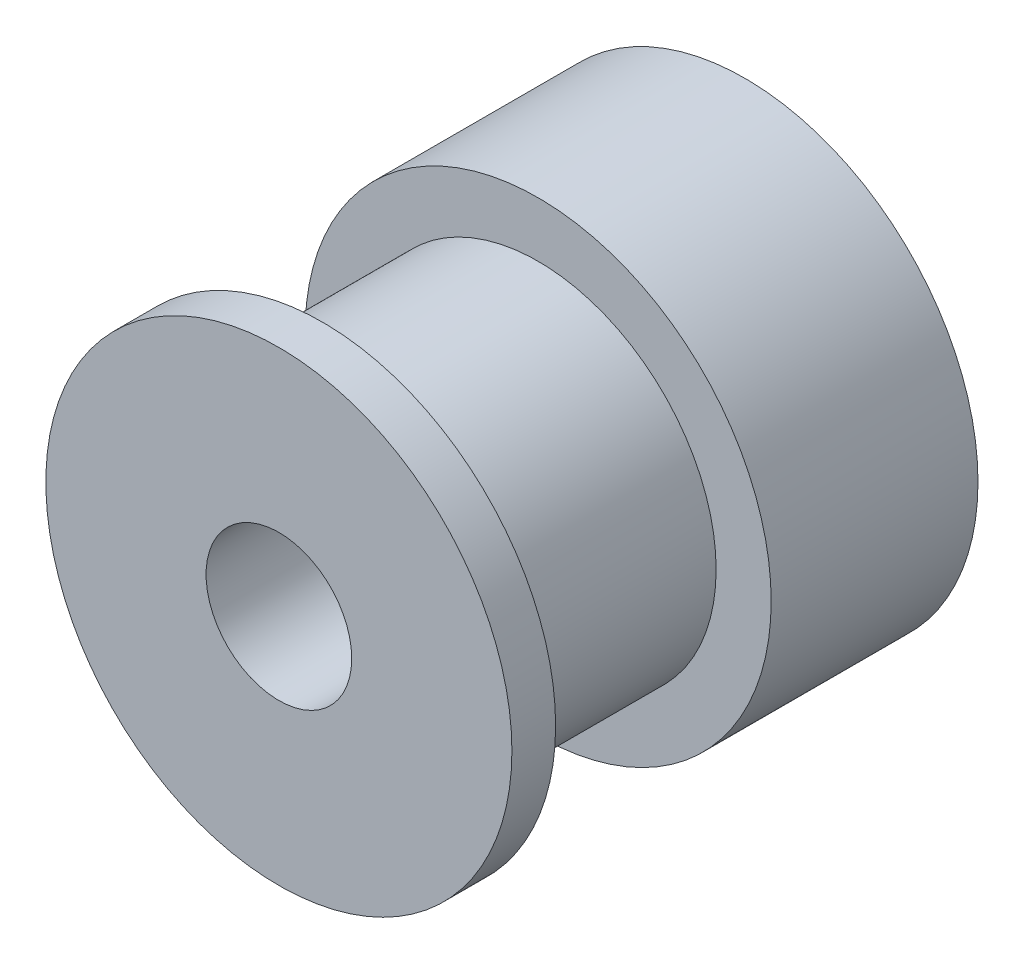
SolidWorks part; units mm, degrees
ref_plane "Front Plane" through (0, 0, 0) normal (0, 0, 1) x (1, 0, 0)
ref_plane "Top Plane" through (0, 0, 0) normal (0, 1, 0) x (1, 0, 0)
ref_plane "Right Plane" through (0, 0, 0) normal (1, 0, 0) x (0, 0, -1)
sketch "Sketch1" plane through (0, 0, 0) normal (0, 0, 1) x (1, 0, 0)
  circle A0 centre (0, 0) radius 8
  dimension "D1" = 16
extrude "Boss-Extrude1" add sketch "Sketch1" along normal blind 7.1
sketch "Sketch2" plane through (0, 0, 7.1) normal (0, 0, 1) x (1, 0, 0)
  circle A0 centre (0, 0) radius 6.11
  dimension "D1" = 12.22
extrude "Boss-Extrude2" add sketch "Sketch2" along normal blind 7.4
sketch "Sketch3" plane through (0, 0, 14.5) normal (0, 0, 1) x (1, 0, 0)
  circle A0 centre (0, 0) radius 8
  dimension "D1" = 16
extrude "Boss-Extrude3" add sketch "Sketch3" along normal blind 1.5
sketch "Sketch4" plane through (0, 0, 16) normal (0, 0, 1) x (1, 0, 0)
  circle A0 centre (0, 0) radius 2.5
  dimension "D1" = 5
extrude "Cut-Extrude1" cut sketch "Sketch4" against normal through all
